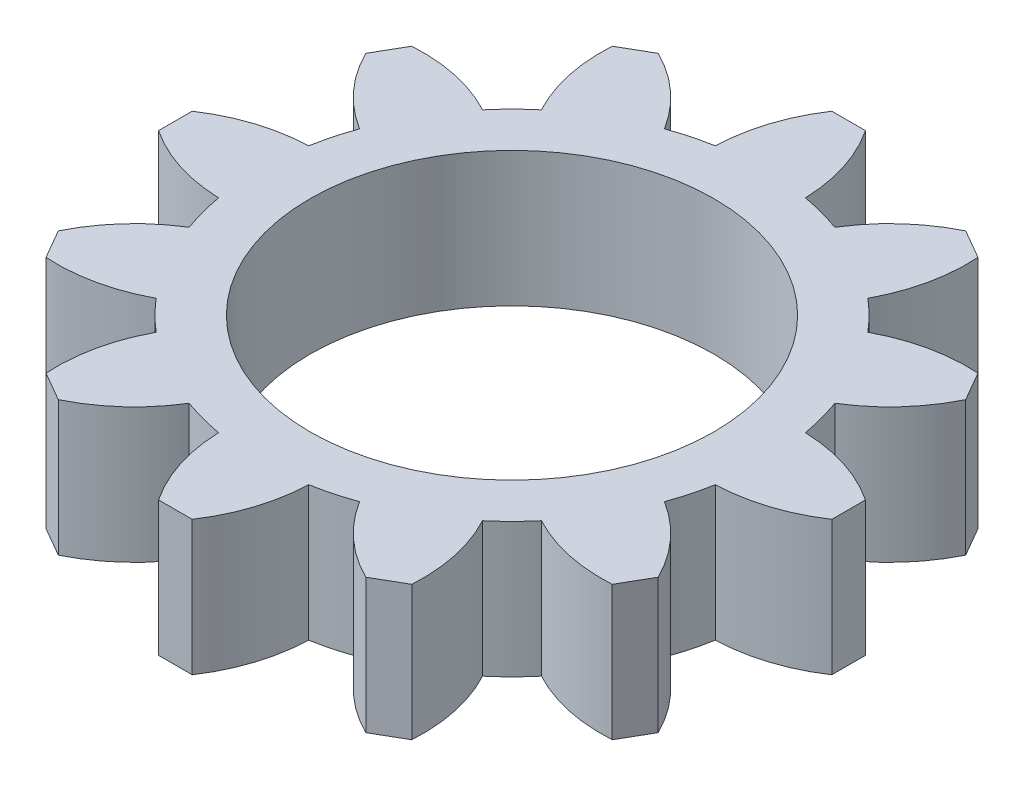
SolidWorks part; units mm, degrees
ref_plane "Front Plane" through (0, 0, 0) normal (0, 0, 1) x (1, 0, 0)
ref_plane "Top Plane" through (0, 0, 0) normal (0, 1, 0) x (1, 0, 0)
ref_plane "Right Plane" through (0, 0, 0) normal (1, 0, 0) x (0, 0, -1)
sketch "Sketch1" plane through (0, 0, 0) normal (0, 1, 0) x (1, 0, 0)
  line L0 (0, 0) -> (0, 21.484) construction
  line L1 (-1, 20) -> (1, 20)
  line L2 (9.134, 17.8205) -> (10.866, 16.8205)
  line L3 (16.8205, 10.866) -> (17.8205, 9.134)
  line L4 (20, 1) -> (20, -1)
  line L5 (17.8205, -9.134) -> (16.8205, -10.866)
  line L6 (10.866, -16.8205) -> (9.134, -17.8205)
  line L7 (1, -20) -> (-1, -20)
  line L8 (-9.134, -17.8205) -> (-10.866, -16.8205)
  line L9 (-16.8205, -10.866) -> (-17.8205, -9.134)
  line L10 (-20, -1) -> (-20, 1)
  line L11 (-17.8205, 9.134) -> (-16.8205, 10.866)
  line L12 (-10.866, 16.8205) -> (-9.134, 17.8205)
  circle A0 centre (0, 0) radius 12
  arc A1 (-2.675, 14.7596) -> (-5.0632, 14.1196) centre (0, 0) ccw
  arc A2 (-1, 20) -> (-2.675, 14.7596) centre (7.3203, 14.4527) ccw
  arc A3 (1, 20) -> (2.675, 14.7596) centre (-7.3203, 14.4527) cw
  arc A4 (9.134, 17.8205) -> (5.0632, 14.1196) centre (13.5659, 8.8562) ccw
  arc A5 (10.866, 16.8205) -> (9.6964, 11.4446) centre (0.8868, 16.1765) cw
  arc A6 (16.8205, 10.866) -> (11.4446, 9.6964) centre (16.1765, 0.8868) ccw
  arc A7 (17.8205, 9.134) -> (14.1196, 5.0632) centre (8.8562, 13.5659) cw
  arc A8 (20, 1) -> (14.7596, 2.675) centre (14.4527, -7.3203) ccw
  arc A9 (20, -1) -> (14.7596, -2.675) centre (14.4527, 7.3203) cw
  arc A10 (17.8205, -9.134) -> (14.1196, -5.0632) centre (8.8562, -13.5659) ccw
  arc A11 (16.8205, -10.866) -> (11.4446, -9.6964) centre (16.1765, -0.8868) cw
  arc A12 (10.866, -16.8205) -> (9.6964, -11.4446) centre (0.8868, -16.1765) ccw
  arc A13 (9.134, -17.8205) -> (5.0632, -14.1196) centre (13.5659, -8.8562) cw
  arc A14 (1, -20) -> (2.675, -14.7596) centre (-7.3203, -14.4527) ccw
  arc A15 (-1, -20) -> (-2.675, -14.7596) centre (7.3203, -14.4527) cw
  arc A16 (-9.134, -17.8205) -> (-5.0632, -14.1196) centre (-13.5659, -8.8562) ccw
  arc A17 (-10.866, -16.8205) -> (-9.6964, -11.4446) centre (-0.8868, -16.1765) cw
  arc A18 (-16.8205, -10.866) -> (-11.4446, -9.6964) centre (-16.1765, -0.8868) ccw
  arc A19 (-17.8205, -9.134) -> (-14.1196, -5.0632) centre (-8.8562, -13.5659) cw
  arc A20 (-20, -1) -> (-14.7596, -2.675) centre (-14.4527, 7.3203) ccw
  arc A21 (-20, 1) -> (-14.7596, 2.675) centre (-14.4527, -7.3203) cw
  arc A22 (-17.8205, 9.134) -> (-14.1196, 5.0632) centre (-8.8562, 13.5659) ccw
  arc A23 (-16.8205, 10.866) -> (-11.4446, 9.6964) centre (-16.1765, 0.8868) cw
  arc A24 (-10.866, 16.8205) -> (-9.6964, 11.4446) centre (-0.8868, 16.1765) ccw
  arc A25 (-9.134, 17.8205) -> (-5.0632, 14.1196) centre (-13.5659, 8.8562) cw
  arc A26 (5.0632, 14.1196) -> (2.675, 14.7596) centre (0, 0) ccw
  arc A27 (11.4446, 9.6964) -> (9.6964, 11.4446) centre (0, 0) ccw
  arc A28 (-9.6964, 11.4446) -> (-11.4446, 9.6964) centre (0, 0) ccw
  arc A29 (-14.1196, 5.0632) -> (-14.7596, 2.675) centre (0, 0) ccw
  arc A30 (-5.0632, -14.1196) -> (-2.675, -14.7596) centre (0, 0) ccw
  arc A31 (-11.4446, -9.6964) -> (-9.6964, -11.4446) centre (0, 0) ccw
  arc A32 (-14.7596, -2.675) -> (-14.1196, -5.0632) centre (0, 0) ccw
  arc A33 (2.675, -14.7596) -> (5.0632, -14.1196) centre (0, 0) ccw
  arc A34 (9.6964, -11.4446) -> (11.4446, -9.6964) centre (0, 0) ccw
  arc A35 (14.1196, -5.0632) -> (14.7596, -2.675) centre (0, 0) ccw
  arc A36 (14.7596, 2.675) -> (14.1196, 5.0632) centre (0, 0) ccw
  point P80 (0, 0)
  dimension "D1" = 30
  dimension "D2" = 24
  dimension "D5" = 10
  dimension "D3" = 2
  dimension "D4" = 20
  dimension "D6" = 5.35
  dimension "D7" = 12
extrude "Boss-Extrude1" add sketch "Sketch1" along normal mid plane 8
